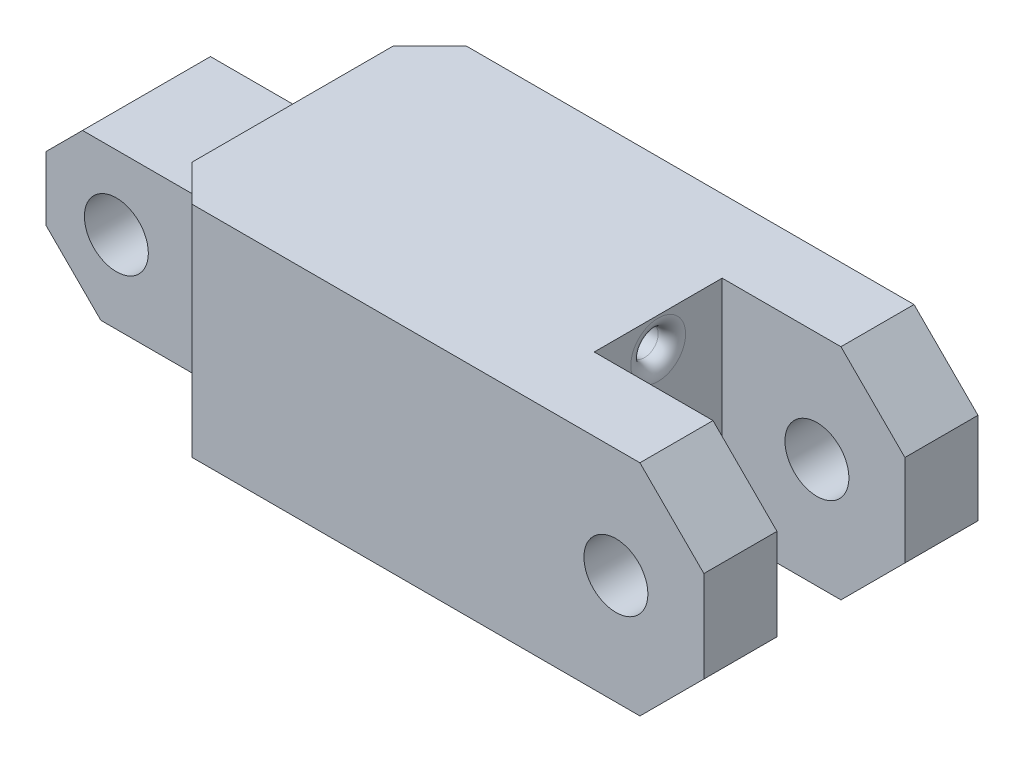
SolidWorks part; units mm, degrees
ref_plane "Спереди" through (0, 0, 0) normal (0, 0, 1) x (1, 0, 0)
ref_plane "Сверху" through (0, 0, 0) normal (0, 1, 0) x (1, 0, 0)
ref_plane "Справа" through (0, 0, 0) normal (1, 0, 0) x (0, 0, -1)
sketch "Эскиз2" plane through (0, 0, 0) normal (1, 0, 0) x (0, 0, -1)
  line L1 (-7.5, 6) -> (7.5, 6)
  line L2 (-7.5, 6) -> (-7.5, -6)
  line L3 (-7.5, -6) -> (7.5, -6)
  line L4 (7.5, 6) -> (7.5, -6)
  line L5 (-7.5, 6) -> (7.5, -6) construction
  line L6 (-7.5, -6) -> (7.5, 6) construction
  point P0 (0, 0)
extrude "Вытянуть1" add sketch "Эскиз2" along normal blind 40
sketch "Эскиз3" plane through (0, 6, 0) normal (0, 1, 0) x (1, 0, 0)
  line L0 (0, 0) -> (-9.2006, 0) construction
  line L1 (10, -9.9613) -> (10, -3.5)
  line L2 (-3.345, 9.9613) -> (10, 9.9613)
  line L3 (-3.345, 9.9613) -> (-3.345, 3.5)
  line L4 (-3.345, 3.5) -> (10, 3.5)
  line L5 (10, 9.9613) -> (10, 3.5)
  line L6 (-3.345, -9.9613) -> (10, -9.9613)
  line L7 (-3.345, -3.5) -> (10, -3.5)
  line L8 (-3.345, -9.9613) -> (-3.345, -3.5)
  line L9 (0, 7.5) -> (0, -7.5) construction
  dimension "D1" = 3.5
  dimension "D2" = 10
extrude "Вырез-Вытянуть1" cut sketch "Эскиз3" against normal through all
sketch "Эскиз4" plane through (0, 0, 3.5) normal (0, 0, 1) x (1, 0, 0)
  circle A0 centre (3.8499, -1.5209) radius 1.75
extrude "Вытянуть2" cut sketch "Эскиз4" against normal through all
sketch "Эскиз5" plane through (0, 6, 0) normal (0, 1, 0) x (1, 0, 0)
  line L0 (40, 0) -> (51.6105, 0) construction
  line L2 (40, 7.5) -> (40, -7.5) construction
  line L3 (30, 3.5) -> (45.3677, 3.5)
  line L4 (30, 3.5) -> (30, -3.5)
  line L5 (30, -3.5) -> (45.3677, -3.5)
  line L6 (45.3677, 3.5) -> (45.3677, -3.5)
  line L7 (30, 3.5) -> (45.3677, -3.5) construction
  line L8 (30, -3.5) -> (45.3677, 3.5) construction
  point P1 (37.6838, 0)
  dimension "D1" = 10
extrude "Вырез-Вытянуть2" cut sketch "Эскиз5" against normal through all
chamfer "Фаска4" distance 3.5 angle 45 4 edges at (40, -6, -5.5) (40, -6, 5.5) (40, 6, -5.5) (40, 6, 5.5)
sketch "Эскиз7" plane through (30, 0, 0) normal (1, 0, 0) x (0, 0, -1)
  line L0 (0, 6) -> (0, 3.9395) construction
  circle A0 centre (0, 4.3577) radius 0.75
extrude "Вытянуть3" cut sketch "Эскиз7" against normal through all
chamfer "Фаска5" distance 3 angle 45 1 edges at (0, -6, 0)
sketch "Эскиз8" plane through (0, 0, 0) normal (-1, 0, 0) x (0, 0, 1)
  line L0 (0, 6) -> (0, 2.0994) construction
  line L2 (-3.5, 6) -> (-7.5, 6) construction
  line L3 (-11.3987, 6.3642) -> (9.5199, 6.3642)
  line L4 (-11.3987, 6.3642) -> (-11.3987, 2.5)
  line L5 (-11.3987, 2.5) -> (9.5199, 2.5)
  line L6 (9.5199, 6.3642) -> (9.5199, 2.5)
  dimension "D1" = 3.5
extrude "Вытянуть4" cut sketch "Эскиз8" against normal blind 10
chamfer "Фаска6" distance 2 angle 45 1 edges at (0, 2.5, 0)
sketch "Эскиз9" plane through (0, 0, 7.5) normal (0, 0, 1) x (1, 0, 0)
  line L0 (35.3234, 0) -> (54.4359, 0) construction
  circle A0 centre (35.1857, 0) radius 1.75
extrude "Вытянуть5" cut sketch "Эскиз9" against normal through all
fillet "Скругление6" radius 0.75 2 edges at (30, 4.3577, -0.75) (10, 4.3577, 0.75)
chamfer "Фаска7" distance 2 angle 45 2 edges at (10, 0, -7.5) (10, 0, 7.5)
